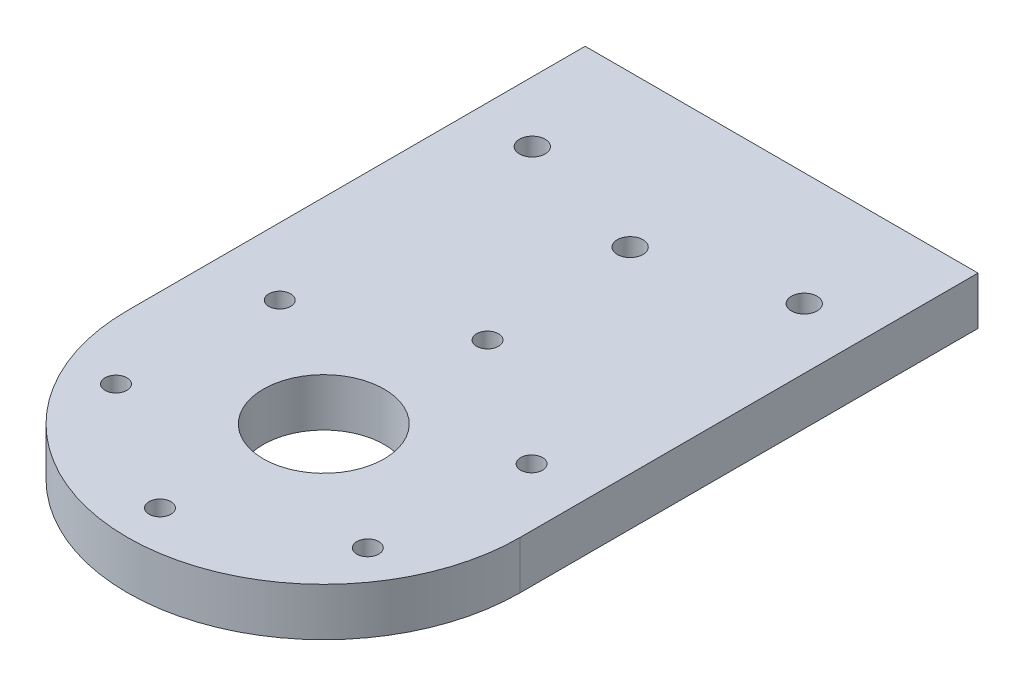
SolidWorks part; units mm, degrees
material "Aleación 6061"
ref_plane "Alzado" through (0, 0, 0) normal (0, 0, 1) x (1, 0, 0)
ref_plane "Planta" through (0, 0, 0) normal (0, 1, 0) x (1, 0, 0)
ref_plane "Vista lateral" through (0, 0, 0) normal (1, 0, 0) x (0, 0, -1)
sketch "Croquis1" plane through (0, 0, 0) normal (0, 1, 0) x (1, 0, 0)
  line L1 (126.4, -275.95) -> (178.4, -275.95)
  line L2 (126.4, -275.95) -> (126.4, -336.55)
  line L3 (126.4, -336.55) -> (178.4, -336.55)
  line L4 (178.4, -275.95) -> (178.4, -336.55)
  dimension "D1" = 126.4
  dimension "D2" = 275.95
  dimension "D3" = 178.4
  dimension "D4" = 275.95
  dimension "D5" = 126.4
  dimension "D6" = 336.55
  dimension "D7" = 178.4
  dimension "D8" = 336.55
extrude "Pared_A_motor_J5" add sketch "Croquis1" along normal blind 6.35 from offset 50.525
sketch "Croquis2" plane through (0, 0, 0) normal (0, 1, 0) x (1, 0, 0)
  circle A0 centre (152.4, -336.55) radius 26
  dimension "D1" = 52
  dimension "D2" = 152.4
  dimension "D3" = 336.55
extrude "Pared_A_motor_J5_redondeo" add sketch "Croquis2" along normal blind 6.35 from offset 50.525
sketch "Croquis3" plane through (0, 0, 0) normal (0, 1, 0) x (1, 0, 0)
  circle A0 centre (169.5144, -347.8349) radius 1.45
  circle A1 centre (151.1842, -357.0139) radius 1.45
  circle A2 centre (134.0698, -345.7291) radius 1.45
  circle A3 centre (135.2856, -325.2651) radius 1.45
  circle A4 centre (153.6158, -316.0861) radius 1.45
  circle A5 centre (170.7302, -327.3709) radius 1.45
  circle A6 centre (152.4, -336.55) radius 8
  dimension "D1" = 2.9
  dimension "D2" = 2.9
  dimension "D3" = 2.9
  dimension "D4" = 2.9
  dimension "D5" = 2.9
  dimension "D6" = 2.9
  dimension "D7" = 16
  dimension "D8" = 169.5144
  dimension "D9" = 347.8349
  dimension "D10" = 151.1842
  dimension "D11" = 357.0139
  dimension "D12" = 134.0698
  dimension "D13" = 345.7291
  dimension "D14" = 135.2856
  dimension "D15" = 325.2651
  dimension "D16" = 153.6158
  dimension "D17" = 316.0861
  dimension "D18" = 170.7302
  dimension "D19" = 327.3709
  dimension "D20" = 152.4
  dimension "D21" = 336.55
extrude "Barrenos_M5" cut sketch "Croquis3" along normal blind 6.35 from offset 50.525
sketch "Croquis4" plane through (0, 0, 0) normal (0, 1, 0) x (1, 0, 0)
  circle A0 centre (134.4, -290.95) radius 1.25
  circle A1 centre (170.4, -290.95) radius 1.25
  dimension "D1" = 2.5
  dimension "D2" = 2.5
  dimension "D3" = 134.4
  dimension "D4" = 290.95
  dimension "D5" = 170.4
  dimension "D6" = 290.95
extrude "Rosca_M3_escuadras" cut sketch "Croquis4" along normal blind 6.35 from offset 50.525
sketch "Croquis5" plane through (0, 0, 0) normal (0, 0, 1) x (1, 0, 0)
  circle A0 centre (130.4, 53.7) radius 2
  circle A1 centre (174.4, 53.7) radius 2
  dimension "D1" = 4
  dimension "D2" = 4
  dimension "D3" = 130.4
  dimension "D4" = 53.7
  dimension "D5" = 174.4
  dimension "D6" = 53.7
extrude "Pasadores_D4" cut sketch "Croquis5" along normal blind 8 from offset 275.95
sketch "Croquis6" plane through (0, 0, 0) normal (0, 1, 0) x (1, 0, 0)
  circle A0 centre (152.4, -296) radius 1.25
  dimension "D1" = 2.5
  dimension "D2" = 152.4
  dimension "D3" = 296
extrude "Rosca_M3_bases_cincho" cut sketch "Croquis6" along normal blind 6.35 from offset 50.525
sketch "Croquis7" plane through (0, 0, 0) normal (0, 1, 0) x (1, 0, 0)
  circle A0 centre (134.4, -290.95) radius 1.7
  circle A1 centre (170.4, -290.95) radius 1.7
  dimension "D1" = 3.4
  dimension "D2" = 3.4
  dimension "D3" = 134.4
  dimension "D4" = 290.95
  dimension "D5" = 170.4
  dimension "D6" = 290.95
extrude "Paso_M3_escuadras_tuerca" cut sketch "Croquis7" along normal blind 6.35 from offset 50.525
sketch "Croquis8" plane through (0, 0, 0) normal (0, 1, 0) x (1, 0, 0)
  circle A0 centre (152.4, -296) radius 1.7
  dimension "D1" = 3.4
  dimension "D2" = 152.4
  dimension "D3" = 296
extrude "Paso_M3_base_cincho_tuerca" cut sketch "Croquis8" along normal blind 6.35 from offset 50.525
